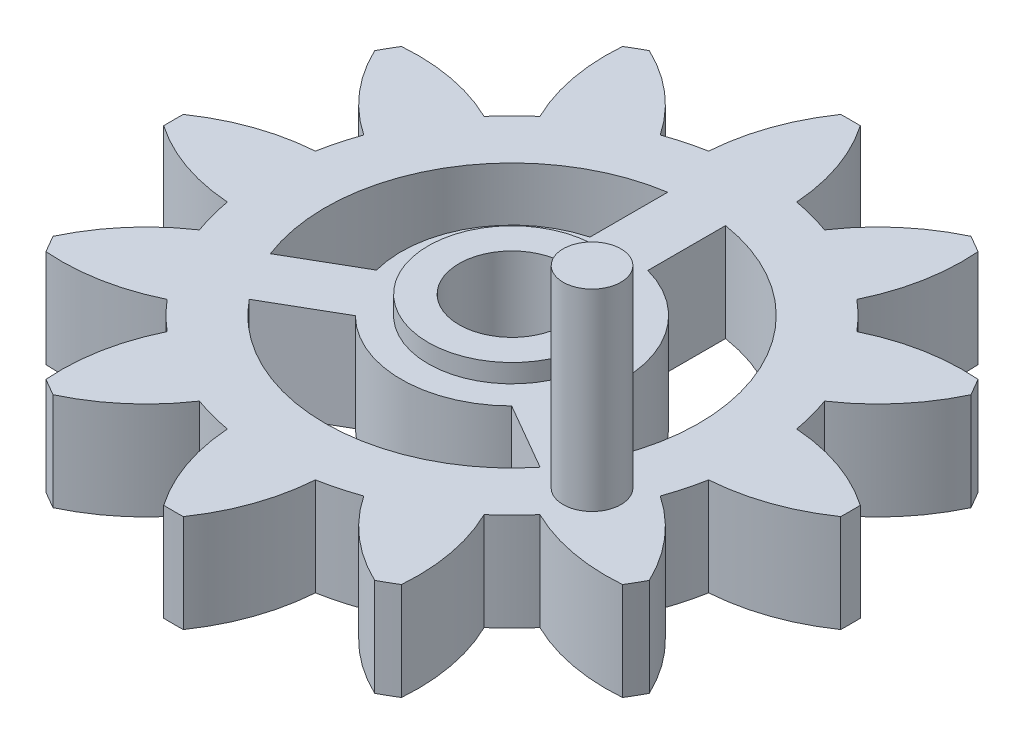
SolidWorks part; units mm, degrees
ref_plane "Front Plane" through (0, 0, 0) normal (0, 0, 1) x (1, 0, 0)
ref_plane "Top Plane" through (0, 0, 0) normal (0, 1, 0) x (1, 0, 0)
ref_plane "Right Plane" through (0, 0, 0) normal (1, 0, 0) x (0, 0, -1)
sketch "Base Profile" plane through (0, 0, 0) normal (0, 1, 0) x (1, 0, 0)
  circle A0 centre (0, 0) radius 12.7
  dimension "D1" = 25.4
extrude "Gear Base" add sketch "Base Profile" along normal mid plane 5.08
sketch "Tooth Profile" plane through (0, 0, 0) normal (0, 1, 0) x (1, 0, 0)
  line L0 (-0.508, 17.5726) -> (0.508, 17.5726) construction
  line L1 (0, 17.5726) -> (0, -12.9032) construction
  circle A0 centre (0, -12.9032) radius 30.48 construction
  arc A1 (-2.286, 12.4926) -> (-0.508, 17.5726) centre (7.8501, 11.7961) cw
  circle A2 centre (0, 0) radius 12.7 construction
  arc A3 (-0.508, 17.5726) -> (0.508, 17.5726) centre (0, -12.9032) cw
  arc A4 (2.286, 12.4926) -> (0.508, 17.5726) centre (-7.8501, 11.7961) ccw
  arc A5 (-2.286, 12.4926) -> (2.286, 12.4926) centre (0, 0) cw
  dimension "D1" = 60.96
  dimension "D2" = 10.16
  dimension "D3" = 1.016
  dimension "D4" = 5.08
  dimension "D5" = 4.572
extrude "Gear Tooth" add sketch "Tooth Profile" against normal up to surface (5.08 mm away) from surface at 2.54 up to face at (0, -2.54, 12.7) starting at face at (0, 2.54, 12.7)
pattern_circular "Pattern Tooth (12T)" count 12 over 360 about axis through (0, 0, 0) along (0, 1, 0) of "Gear Tooth"
sketch "Lip Profile" plane through (0, 0, 0) normal (0, 1, 0) x (1, 0, 0)
  circle A0 centre (0, 0) radius 4.3484
  dimension "D1" = 8.6967
extrude "Lip" add sketch "Lip Profile" along normal mid plane 7
sketch "Hole Profile" plane through (0, 2.54, 0) normal (0, 1, 0) x (1, 0, 0)
  circle A0 centre (0, 0) radius 2.75
  dimension "D1" = 5.5
extrude "Shaft Hole" cut sketch "Hole Profile" against normal up to surface (7 mm away) from surface at 0.96 up to face at (0, -3.5, 4.3484) starting at face at (0, 3.5, 4.3484)
sketch "Cutout Profile" plane through (0, 2.54, 0) normal (0, 1, 0) x (1, 0, 0)
  line L0 (-1.5, 9.5833) -> (-1.5, 5.5509)
  line L1 (1.5, 9.5833) -> (1.5, 5.5509)
  line L2 (-1.5, 9.5833) -> (1.5, 9.5833) construction
  line L3 (0, 9.5833) -> (0, 0) construction
  line L4 (9.0494, -3.4926) -> (5.5572, -1.4764)
  line L5 (7.5494, -6.0907) -> (4.0572, -4.0745)
  line L6 (-7.5494, -6.0907) -> (-4.0572, -4.0745)
  line L7 (-9.0494, -3.4926) -> (-5.5572, -1.4764)
  arc A0 (-7.5494, -6.0907) -> (7.5494, -6.0907) centre (0, 0) ccw
  arc A1 (-1.5, 5.5509) -> (-5.5572, -1.4764) centre (0, 0) ccw
  circle A2 centre (0, 0) radius 2.75 construction
  arc A3 (4.2665, 11.9619) -> (2.286, 12.4926) centre (0, 0) ccw construction
  arc A4 (9.0494, -3.4926) -> (1.5, 9.5833) centre (0, 0) ccw
  arc A5 (-1.5, 9.5833) -> (-9.0494, -3.4926) centre (0, 0) ccw
  arc A6 (-4.0572, -4.0745) -> (4.0572, -4.0745) centre (0, 0) ccw
  arc A7 (5.5572, -1.4764) -> (1.5, 5.5509) centre (0, 0) ccw
  dimension "D1" = 3
  dimension "D2" = 3
  dimension "D3" = 3
  dimension "D4" = 3
extrude "Gear Cutout" cut sketch "Cutout Profile" against normal up to surface (5.08 mm away) up to face at (0, -2.54, 4.3484)
sketch "Handle Profile" plane through (0, 2.54, 0) normal (0, 1, 0) x (1, 0, 0)
  line L0 (5.5572, -1.4764) -> (9.0494, -3.4926) construction
  line L1 (7.5494, -6.0907) -> (4.0572, -4.0745) construction
  line L2 (5.5572, -1.4764) -> (4.0572, -4.0745) construction
  line L3 (4.8072, -2.7755) -> (9.8302, -5.6755) construction
  circle A0 centre (9.8302, -5.6755) radius 1.5
  dimension "D1" = 5.8
extrude "Handle" add sketch "Handle Profile" along normal blind 10
